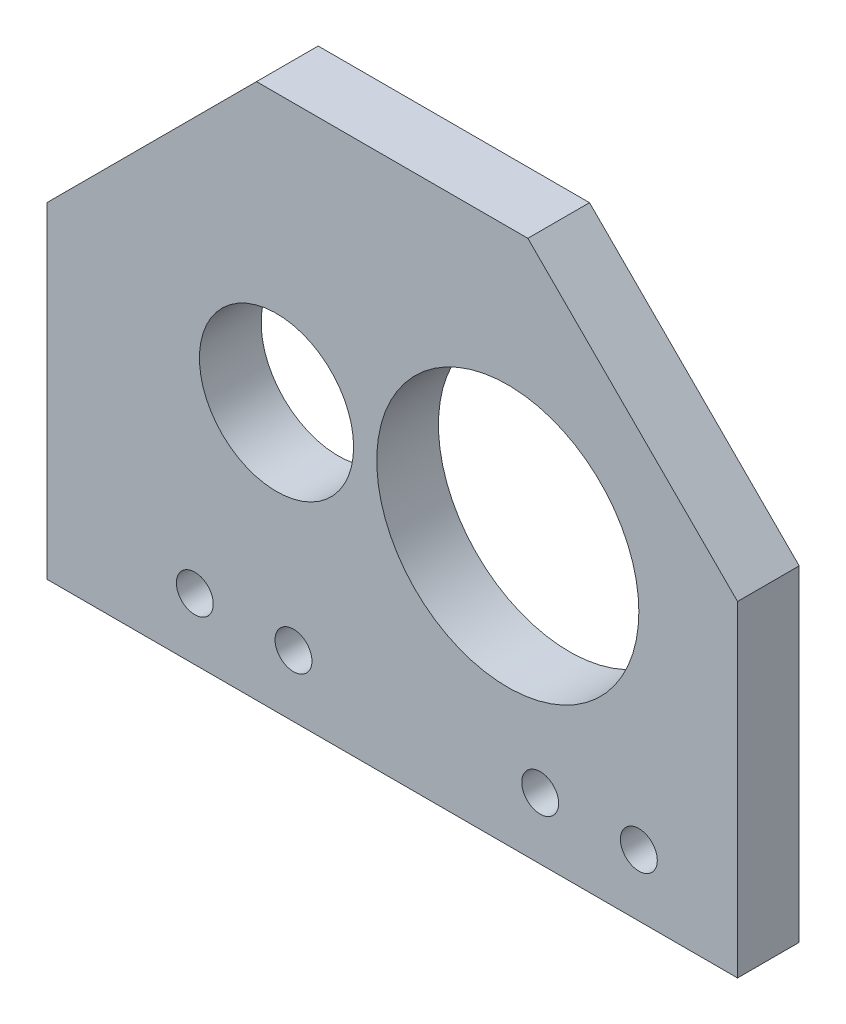
SolidWorks part; units mm, degrees
ref_plane "Front Plane" through (0, 0, 0) normal (0, 0, 1) x (1, 0, 0)
ref_plane "Top Plane" through (0, 0, 0) normal (0, 1, 0) x (1, 0, 0)
ref_plane "Right Plane" through (0, 0, 0) normal (1, 0, 0) x (0, 0, -1)
sketch "Sketch1" plane through (0, 0, 0) normal (0, 0, 1) x (1, 0, 0)
  line L1 (35.56, -27.5819) -> (-35.56, -27.5819)
  line L2 (35.56, -27.5819) -> (35.56, 27.5819)
  line L3 (35.56, 27.5819) -> (-35.56, 27.5819)
  line L4 (-35.56, -27.5819) -> (-35.56, 27.5819)
  line L5 (35.56, -27.5819) -> (-35.56, 27.5819) construction
  line L6 (35.56, 27.5819) -> (-35.56, -27.5819) construction
  circle A0 centre (11.9062, 0) radius 13.4937
  circle A1 centre (-11.9062, 0) radius 7.9375
  point P0 (0, 0)
  dimension "D3" = 26.9875
  dimension "D6" = 15.875
  dimension "D1" = 71.12
  dimension "D2" = 55.1637
  dimension "D4" = 0
  dimension "D5" = 0
  dimension "D7" = 11.9062
  dimension "D8" = 11.9062
extrude "Boss-Extrude1" add sketch "Sketch1" along normal blind 6.35
hole_wizard "#6 Clearance Hole1" positions "Sketch2" profile "Sketch3" hole size "#6" standard "ANSI Inch" end condition through all
sketch "Sketch2" plane through (0, 0, 6.35) normal (0, 0, 1) x (1, 0, 0)
  line L1 (-20.32, -21.2319) -> (-10.16, -21.2319)
  line L3 (15.24, -21.2319) -> (25.4, -21.2319)
  line L5 (-35.56, -27.5819) -> (35.56, -27.5819) construction
  line L6 (-35.56, 27.5819) -> (-35.56, -27.5819) construction
  line L7 (35.56, -27.5819) -> (35.56, 27.5819) construction
  point P0 (-20.32, -21.2319)
  point P2 (-10.16, -21.2319)
  point P4 (15.24, -21.2319)
  point P6 (25.4, -21.2319)
  dimension "D1" = 10.16
  dimension "D2" = 10.16
  dimension "D3" = 6.35
  dimension "D4" = 6.35
  dimension "D5" = 15.24
  dimension "D6" = 10.16
sketch "Sketch3" plane through (-20.32, -21.2319, 6.35) normal (1, 0, 0) x (0, -1, 0)
  line L0 (0, 0) -> (0, 6.35)
  line L1 (0, 6.35) -> (1.8986, 6.35)
  line L2 (1.8986, 6.35) -> (1.8986, 0)
  line L5 (1.8986, 0) -> (0, 0)
  line L11 (0, -6.35) -> (0, 107.95) construction
  dimension "Thru Hole Dia." = 3.7973
  dimension "Thru Hole Depth" = 6.35
sketch "Sketch4" plane through (0, 0, 6.35) normal (0, 0, 1) x (1, 0, 0)
  line L0 (-35.56, 5.9919) -> (-13.97, 27.5819)
  line L1 (-35.56, 27.5819) -> (-35.56, -27.5819) construction
  line L2 (35.56, 27.5819) -> (-35.56, 27.5819) construction
  line L3 (35.56, 5.9919) -> (13.97, 27.5819)
  line L4 (35.56, -27.5819) -> (35.56, 27.5819) construction
  line L5 (-35.56, 27.5819) -> (-35.56, 5.9919)
  line L6 (-13.97, 27.5819) -> (-35.56, 27.5819)
  line L7 (13.97, 27.5819) -> (35.56, 27.5819)
  line L8 (35.56, 27.5819) -> (35.56, 5.9919)
  dimension "D1" = 21.59
  dimension "D2" = 21.59
  dimension "D3" = 21.59
  dimension "D4" = 21.59
extrude "Cut-Extrude1" cut sketch "Sketch4" against normal through all
